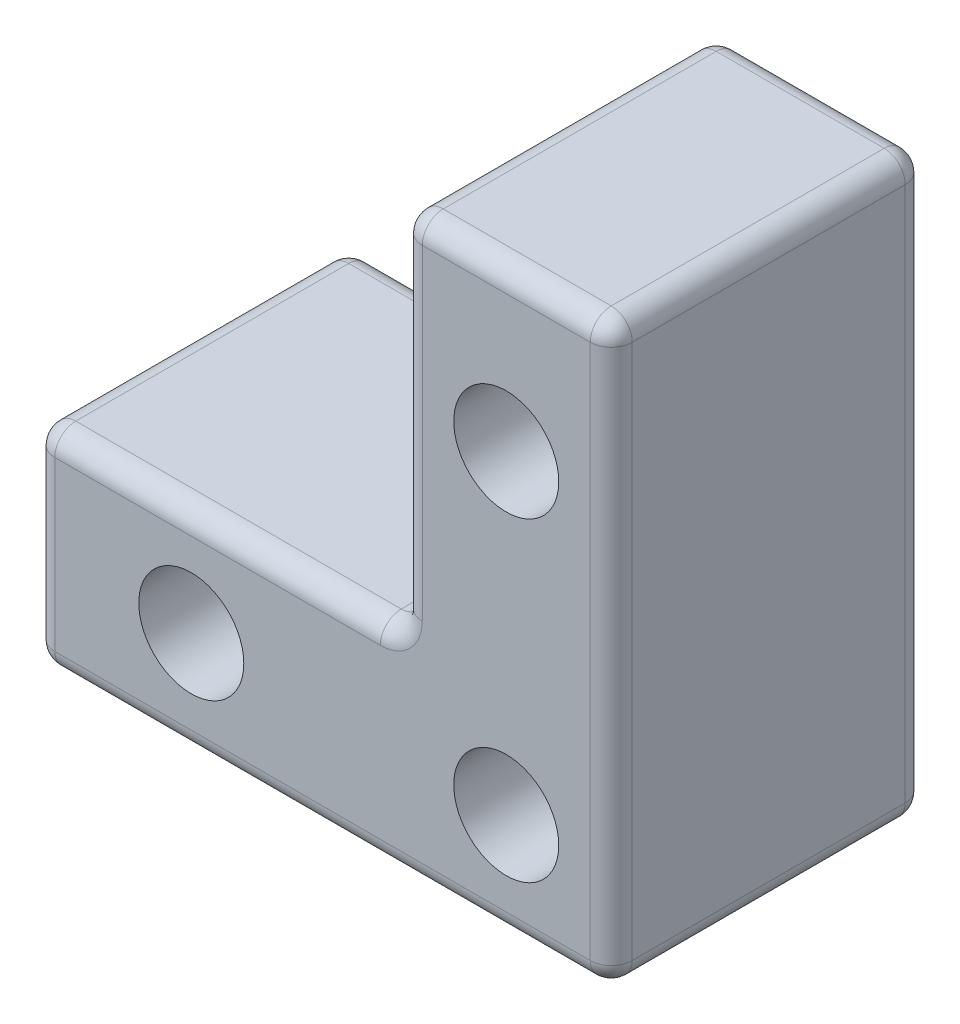
SolidWorks part; units mm, degrees
ref_plane "前视基准面" through (0, 0, 0) normal (0, 0, 1) x (1, 0, 0)
ref_plane "上视基准面" through (0, 0, 0) normal (0, 1, 0) x (1, 0, 0)
ref_plane "右视基准面" through (0, 0, 0) normal (1, 0, 0) x (0, 0, -1)
sketch "草图1" plane through (0, 0, 0) normal (0, 0, 1) x (1, 0, 0)
  line L0 (30, 20) -> (30, 55)
  line L1 (0, 0) -> (60, 0)
  line L2 (0, 0) -> (0, 20)
  line L3 (0, 20) -> (60, 20)
  line L4 (60, 0) -> (60, 20)
  line L5 (30, 55) -> (60, 55)
  line L6 (60, 55) -> (60, 20)
  line L7 (30, 20) -> (60, 20)
extrude "凸台-拉伸1" add sketch "草图1" along normal blind 30 contours L1 L4 L3 L2 | L6 L5 L0 L3
sketch "草图2" plane through (0, 0, 30) normal (0, 0, 1) x (1, 0, 0)
  line L0 (0, 10) -> (15, 10)
  line L1 (0, 0) -> (0, 20) construction
  line L2 (60, 10) -> (45, 10)
  line L3 (60, 0) -> (60, 55) construction
  line L5 (45, 55) -> (45, 40)
  line L6 (30, 55) -> (60, 55) construction
  circle A0 centre (15, 10) radius 5
  circle A1 centre (45, 10) radius 5
  circle A2 centre (45, 40) radius 5
extrude "切除-拉伸1" cut sketch "草图2" against normal through all
sketch "草图3" plane through (0, 0, 30) normal (0, 0, 1) x (1, 0, 0)
  line L1 (30, 20) -> (35, 20)
  line L3 (60, 0) -> (60, 55) construction
  line L4 (30, 55) -> (30, 20)
  line L5 (30, 55) -> (35, 55)
  line L6 (30, 55) -> (60, 55) construction
  line L7 (35, 55) -> (35, 20)
  line L8 (60, 20) -> (60, 55)
  line L9 (60, 55) -> (55, 55)
  line L10 (55, 55) -> (55, 20)
  line L11 (55, 20) -> (55, 0)
  line L12 (0, 0) -> (60, 0) construction
  line L13 (55, 0) -> (60, 0)
  line L14 (60, 0) -> (60, 20)
extrude "切除-拉伸2" cut sketch "草图3" against normal through all
fillet "圆角1" radius 2 18 edges at (0, 20, 15) (0, 10, 30) (17.5, 20, 30) (55, 27.5, 30) (0, 0, 15) (27.5, 0, 30) (55, 0, 15) (17.5, 20, 0) (0, 10, 0) (27.5, 0, 0) (55, 27.5, 0) (35, 20, 15) (35, 37.5, 30) (35, 37.5, 0) (45, 55, 30) (35, 55, 15) (45, 55, 0) (55, 55, 15)
